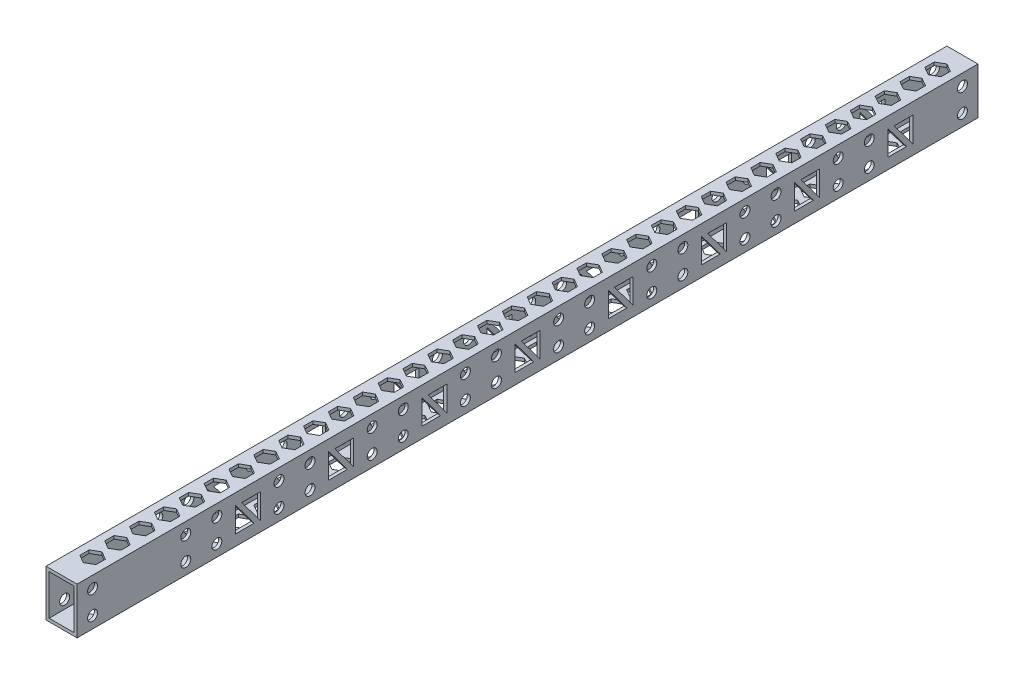
SolidWorks part; units mm, degrees
ref_plane "前视基准面" through (0, 0, 0) normal (0, 0, 1) x (1, 0, 0)
ref_plane "上视基准面" through (0, 0, 0) normal (0, 1, 0) x (1, 0, 0)
ref_plane "右视基准面" through (0, 0, 0) normal (1, 0, 0) x (0, 0, -1)
other "Configuration Table"
sketch "草图1" plane through (0, 0, 0) normal (0, 0, 1) x (1, 0, 0)
  line L1 (0, 0) -> (10, 0)
  line L2 (0, 0) -> (0, -15)
  line L3 (0, -15) -> (10, -15)
  line L4 (10, 0) -> (10, -15)
  dimension "D1" = 10
  dimension "D2" = 15
extrude "拉伸-薄壁1" add sketch "草图1" along normal blind 290 thin
sketch "草图2" plane through (10, 0, 0) normal (1, 0, 0) x (0, 0, -1)
  line L0 (-145, 0) -> (-145, -15) construction
  line L1 (-290, 0) -> (0, 0) construction
  line L3 (-290, -15) -> (0, -15) construction
  line L5 (-290, -7.5) -> (-285, -7.5) construction
  line L6 (-290, -15) -> (-290, 0) construction
  line L7 (-285, -7.5) -> (-285, 0) construction
  line L8 (-5, -7.5) -> (-5, 0) construction
  line L9 (0, -7.5) -> (-5, -7.5) construction
  line L10 (-250, 0) -> (-250, -15) construction
  line L11 (-239, -3.5) -> (-239, -11.5)
  line L12 (-239, -11.5) -> (-233, -11.5)
  line L13 (-233, -11.5) -> (-239, -3.5)
  line L14 (-237, -3.75) -> (-231, -3.75)
  line L15 (-231, -3.75) -> (-231, -11.75)
  line L16 (-231, -11.75) -> (-237, -3.75)
  line L17 (-201, -3.75) -> (-201, -11.75)
  line L18 (-207, -3.75) -> (-201, -3.75)
  line L19 (-201, -11.75) -> (-207, -3.75)
  line L20 (-203, -11.5) -> (-209, -3.5)
  line L21 (-209, -3.5) -> (-209, -11.5)
  line L22 (-209, -11.5) -> (-203, -11.5)
  line L23 (-171, -3.75) -> (-171, -11.75)
  line L24 (-177, -3.75) -> (-171, -3.75)
  line L25 (-171, -11.75) -> (-177, -3.75)
  line L26 (-173, -11.5) -> (-179, -3.5)
  line L27 (-179, -3.5) -> (-179, -11.5)
  line L28 (-179, -11.5) -> (-173, -11.5)
  line L29 (-141, -3.75) -> (-141, -11.75)
  line L30 (-147, -3.75) -> (-141, -3.75)
  line L31 (-141, -11.75) -> (-147, -3.75)
  line L32 (-143, -11.5) -> (-149, -3.5)
  line L33 (-149, -3.5) -> (-149, -11.5)
  line L34 (-149, -11.5) -> (-143, -11.5)
  line L35 (-111, -3.75) -> (-111, -11.75)
  line L36 (-117, -3.75) -> (-111, -3.75)
  line L37 (-111, -11.75) -> (-117, -3.75)
  line L38 (-113, -11.5) -> (-119, -3.5)
  line L39 (-119, -3.5) -> (-119, -11.5)
  line L40 (-119, -11.5) -> (-113, -11.5)
  line L41 (-81, -3.75) -> (-81, -11.75)
  line L42 (-87, -3.75) -> (-81, -3.75)
  line L43 (-81, -11.75) -> (-87, -3.75)
  line L44 (-83, -11.5) -> (-89, -3.5)
  line L45 (-89, -3.5) -> (-89, -11.5)
  line L46 (-89, -11.5) -> (-83, -11.5)
  line L47 (-51, -3.75) -> (-51, -11.75)
  line L48 (-57, -3.75) -> (-51, -3.75)
  line L49 (-51, -11.75) -> (-57, -3.75)
  line L50 (-53, -11.5) -> (-59, -3.5)
  line L51 (-59, -3.5) -> (-59, -11.5)
  line L52 (-59, -11.5) -> (-53, -11.5)
  line L53 (-21, -3.75) -> (-21, -11.75)
  line L54 (-27, -3.75) -> (-21, -3.75)
  line L55 (-21, -11.75) -> (-27, -3.75)
  line L56 (-23, -11.5) -> (-29, -3.5)
  line L57 (-29, -3.5) -> (-29, -11.5)
  line L58 (-29, -11.5) -> (-23, -11.5)
  circle A4 centre (-285, -3.75) radius 1.6
  circle A5 centre (-285, -11.25) radius 1.6
  circle A6 centre (-5, -11.25) radius 1.6
  circle A7 centre (-5, -3.75) radius 1.6
  circle A8 centre (-255, -3.75) radius 1.6
  circle A9 centre (-255, -11.25) radius 1.6
  circle A10 centre (-245, -11.25) radius 1.6
  circle A11 centre (-245, -3.75) radius 1.6
  circle A12 centre (-225, -3.75) radius 1.6
  circle A13 centre (-215, -3.75) radius 1.6
  circle A14 centre (-215, -11.25) radius 1.6
  circle A15 centre (-225, -11.25) radius 1.6
  circle A16 centre (-195, -3.75) radius 1.6
  circle A17 centre (-185, -3.75) radius 1.6
  circle A18 centre (-185, -11.25) radius 1.6
  circle A19 centre (-195, -11.25) radius 1.6
  circle A20 centre (-165, -3.75) radius 1.6
  circle A21 centre (-155, -3.75) radius 1.6
  circle A22 centre (-155, -11.25) radius 1.6
  circle A23 centre (-165, -11.25) radius 1.6
  circle A24 centre (-135, -3.75) radius 1.6
  circle A25 centre (-125, -3.75) radius 1.6
  circle A26 centre (-125, -11.25) radius 1.6
  circle A27 centre (-135, -11.25) radius 1.6
  circle A28 centre (-105, -3.75) radius 1.6
  circle A29 centre (-95, -3.75) radius 1.6
  circle A30 centre (-95, -11.25) radius 1.6
  circle A31 centre (-105, -11.25) radius 1.6
  circle A32 centre (-75, -3.75) radius 1.6
  circle A33 centre (-65, -3.75) radius 1.6
  circle A34 centre (-65, -11.25) radius 1.6
  circle A35 centre (-75, -11.25) radius 1.6
  circle A36 centre (-45, -3.75) radius 1.6
  circle A37 centre (-35, -3.75) radius 1.6
  circle A38 centre (-35, -11.25) radius 1.6
  circle A39 centre (-45, -11.25) radius 1.6
  dimension "D1" = 40
  dimension "D6" = 3.2
  dimension "D2" = 3.2
  dimension "D3" = 3.75
  dimension "D4" = 5
  dimension "D5" = 5
  dimension "D7" = 3.75
  dimension "D9" = 30
  dimension "D10" = 6
  dimension "D11" = 8
  dimension "D12" = 6
  dimension "D13" = 8
  dimension "D14" = 11
  dimension "D15" = 6
  dimension "D17" = 30
  dimension "D8" = 8
  dimension "D16" = 8
extrude "切除-拉伸1" cut sketch "草图2" against normal through all
sketch "草图3" plane through (0, 0, 0) normal (0, 1, 0) x (1, 0, 0)
  line L0 (5, -8) -> (5, 0) construction
  line L1 (5, -11) -> (7.5981, -9.5)
  line L2 (7.5981, -9.5) -> (7.5981, -6.5)
  line L3 (7.5981, -6.5) -> (5, -5)
  line L4 (5, -5) -> (2.4019, -6.5)
  line L5 (2.4019, -6.5) -> (2.4019, -9.5)
  line L6 (2.4019, -9.5) -> (5, -11)
  line L7 (10, 0) -> (0, 0) construction
  line L8 (5, -13) -> (2.4019, -14.5)
  line L9 (7.5981, -14.5) -> (5, -13)
  line L10 (7.5981, -17.5) -> (7.5981, -14.5)
  line L11 (2.4019, -14.5) -> (2.4019, -17.5)
  line L12 (2.4019, -17.5) -> (5, -19)
  line L13 (5, -19) -> (7.5981, -17.5)
  line L14 (5, -21) -> (2.4019, -22.5)
  line L15 (7.5981, -22.5) -> (5, -21)
  line L16 (7.5981, -25.5) -> (7.5981, -22.5)
  line L17 (2.4019, -22.5) -> (2.4019, -25.5)
  line L18 (2.4019, -25.5) -> (5, -27)
  line L19 (5, -27) -> (7.5981, -25.5)
  line L20 (5, -29) -> (2.4019, -30.5)
  line L21 (7.5981, -30.5) -> (5, -29)
  line L22 (7.5981, -33.5) -> (7.5981, -30.5)
  line L23 (2.4019, -30.5) -> (2.4019, -33.5)
  line L24 (2.4019, -33.5) -> (5, -35)
  line L25 (5, -35) -> (7.5981, -33.5)
  line L26 (5, -37) -> (2.4019, -38.5)
  line L27 (7.5981, -38.5) -> (5, -37)
  line L28 (7.5981, -41.5) -> (7.5981, -38.5)
  line L29 (2.4019, -38.5) -> (2.4019, -41.5)
  line L30 (2.4019, -41.5) -> (5, -43)
  line L31 (5, -43) -> (7.5981, -41.5)
  line L32 (5, -45) -> (2.4019, -46.5)
  line L33 (7.5981, -46.5) -> (5, -45)
  line L34 (7.5981, -49.5) -> (7.5981, -46.5)
  line L35 (2.4019, -46.5) -> (2.4019, -49.5)
  line L36 (2.4019, -49.5) -> (5, -51)
  line L37 (5, -51) -> (7.5981, -49.5)
  line L38 (5, -53) -> (2.4019, -54.5)
  line L39 (7.5981, -54.5) -> (5, -53)
  line L40 (7.5981, -57.5) -> (7.5981, -54.5)
  line L41 (2.4019, -54.5) -> (2.4019, -57.5)
  line L42 (2.4019, -57.5) -> (5, -59)
  line L43 (5, -59) -> (7.5981, -57.5)
  line L44 (5, -61) -> (2.4019, -62.5)
  line L45 (7.5981, -62.5) -> (5, -61)
  line L46 (7.5981, -65.5) -> (7.5981, -62.5)
  line L47 (2.4019, -62.5) -> (2.4019, -65.5)
  line L48 (2.4019, -65.5) -> (5, -67)
  line L49 (5, -67) -> (7.5981, -65.5)
  line L50 (5, -69) -> (2.4019, -70.5)
  line L51 (7.5981, -70.5) -> (5, -69)
  line L52 (7.5981, -73.5) -> (7.5981, -70.5)
  line L53 (2.4019, -70.5) -> (2.4019, -73.5)
  line L54 (2.4019, -73.5) -> (5, -75)
  line L55 (5, -75) -> (7.5981, -73.5)
  line L56 (5, -77) -> (2.4019, -78.5)
  line L57 (7.5981, -78.5) -> (5, -77)
  line L58 (7.5981, -81.5) -> (7.5981, -78.5)
  line L59 (2.4019, -78.5) -> (2.4019, -81.5)
  line L60 (2.4019, -81.5) -> (5, -83)
  line L61 (5, -83) -> (7.5981, -81.5)
  line L62 (5, -85) -> (2.4019, -86.5)
  line L63 (7.5981, -86.5) -> (5, -85)
  line L64 (7.5981, -89.5) -> (7.5981, -86.5)
  line L65 (2.4019, -86.5) -> (2.4019, -89.5)
  line L66 (2.4019, -89.5) -> (5, -91)
  line L67 (5, -91) -> (7.5981, -89.5)
  line L68 (5, -93) -> (2.4019, -94.5)
  line L69 (7.5981, -94.5) -> (5, -93)
  line L70 (7.5981, -97.5) -> (7.5981, -94.5)
  line L71 (2.4019, -94.5) -> (2.4019, -97.5)
  line L72 (2.4019, -97.5) -> (5, -99)
  line L73 (5, -99) -> (7.5981, -97.5)
  line L74 (5, -101) -> (2.4019, -102.5)
  line L75 (7.5981, -102.5) -> (5, -101)
  line L76 (7.5981, -105.5) -> (7.5981, -102.5)
  line L77 (2.4019, -102.5) -> (2.4019, -105.5)
  line L78 (2.4019, -105.5) -> (5, -107)
  line L79 (5, -107) -> (7.5981, -105.5)
  line L80 (5, -109) -> (2.4019, -110.5)
  line L81 (7.5981, -110.5) -> (5, -109)
  line L82 (7.5981, -113.5) -> (7.5981, -110.5)
  line L83 (2.4019, -110.5) -> (2.4019, -113.5)
  line L84 (2.4019, -113.5) -> (5, -115)
  line L85 (5, -115) -> (7.5981, -113.5)
  line L86 (5, -117) -> (2.4019, -118.5)
  line L87 (7.5981, -118.5) -> (5, -117)
  line L88 (7.5981, -121.5) -> (7.5981, -118.5)
  line L89 (2.4019, -118.5) -> (2.4019, -121.5)
  line L90 (2.4019, -121.5) -> (5, -123)
  line L91 (5, -123) -> (7.5981, -121.5)
  line L92 (5, -125) -> (2.4019, -126.5)
  line L93 (7.5981, -126.5) -> (5, -125)
  line L94 (7.5981, -129.5) -> (7.5981, -126.5)
  line L95 (2.4019, -126.5) -> (2.4019, -129.5)
  line L96 (2.4019, -129.5) -> (5, -131)
  line L97 (5, -131) -> (7.5981, -129.5)
  line L98 (5, -133) -> (2.4019, -134.5)
  line L99 (7.5981, -134.5) -> (5, -133)
  line L100 (7.5981, -137.5) -> (7.5981, -134.5)
  line L101 (2.4019, -134.5) -> (2.4019, -137.5)
  line L102 (2.4019, -137.5) -> (5, -139)
  line L103 (5, -139) -> (7.5981, -137.5)
  line L104 (5, -141) -> (2.4019, -142.5)
  line L105 (7.5981, -142.5) -> (5, -141)
  line L106 (7.5981, -145.5) -> (7.5981, -142.5)
  line L107 (2.4019, -142.5) -> (2.4019, -145.5)
  line L108 (2.4019, -145.5) -> (5, -147)
  line L109 (5, -147) -> (7.5981, -145.5)
  line L110 (5, -149) -> (2.4019, -150.5)
  line L111 (7.5981, -150.5) -> (5, -149)
  line L112 (7.5981, -153.5) -> (7.5981, -150.5)
  line L113 (2.4019, -150.5) -> (2.4019, -153.5)
  line L114 (2.4019, -153.5) -> (5, -155)
  line L115 (5, -155) -> (7.5981, -153.5)
  line L116 (5, -157) -> (2.4019, -158.5)
  line L117 (7.5981, -158.5) -> (5, -157)
  line L118 (7.5981, -161.5) -> (7.5981, -158.5)
  line L119 (2.4019, -158.5) -> (2.4019, -161.5)
  line L120 (2.4019, -161.5) -> (5, -163)
  line L121 (5, -163) -> (7.5981, -161.5)
  line L122 (5, -165) -> (2.4019, -166.5)
  line L123 (7.5981, -166.5) -> (5, -165)
  line L124 (7.5981, -169.5) -> (7.5981, -166.5)
  line L125 (2.4019, -166.5) -> (2.4019, -169.5)
  line L126 (2.4019, -169.5) -> (5, -171)
  line L127 (5, -171) -> (7.5981, -169.5)
  line L128 (5, -173) -> (2.4019, -174.5)
  line L129 (7.5981, -174.5) -> (5, -173)
  line L130 (7.5981, -177.5) -> (7.5981, -174.5)
  line L131 (2.4019, -174.5) -> (2.4019, -177.5)
  line L132 (2.4019, -177.5) -> (5, -179)
  line L133 (5, -179) -> (7.5981, -177.5)
  line L134 (5, -181) -> (2.4019, -182.5)
  line L135 (7.5981, -182.5) -> (5, -181)
  line L136 (7.5981, -185.5) -> (7.5981, -182.5)
  line L137 (2.4019, -182.5) -> (2.4019, -185.5)
  line L138 (2.4019, -185.5) -> (5, -187)
  line L139 (5, -187) -> (7.5981, -185.5)
  line L140 (5, -189) -> (2.4019, -190.5)
  line L141 (7.5981, -190.5) -> (5, -189)
  line L142 (7.5981, -193.5) -> (7.5981, -190.5)
  line L143 (2.4019, -190.5) -> (2.4019, -193.5)
  line L144 (2.4019, -193.5) -> (5, -195)
  line L145 (5, -195) -> (7.5981, -193.5)
  line L146 (5, -197) -> (2.4019, -198.5)
  line L147 (7.5981, -198.5) -> (5, -197)
  line L148 (7.5981, -201.5) -> (7.5981, -198.5)
  line L149 (2.4019, -198.5) -> (2.4019, -201.5)
  line L150 (2.4019, -201.5) -> (5, -203)
  line L151 (5, -203) -> (7.5981, -201.5)
  line L152 (5, -205) -> (2.4019, -206.5)
  line L153 (7.5981, -206.5) -> (5, -205)
  line L154 (7.5981, -209.5) -> (7.5981, -206.5)
  line L155 (2.4019, -206.5) -> (2.4019, -209.5)
  line L156 (2.4019, -209.5) -> (5, -211)
  line L157 (5, -211) -> (7.5981, -209.5)
  line L158 (5, -213) -> (2.4019, -214.5)
  line L159 (7.5981, -214.5) -> (5, -213)
  line L160 (7.5981, -217.5) -> (7.5981, -214.5)
  line L161 (2.4019, -214.5) -> (2.4019, -217.5)
  line L162 (2.4019, -217.5) -> (5, -219)
  line L163 (5, -219) -> (7.5981, -217.5)
  line L164 (5, -221) -> (2.4019, -222.5)
  line L165 (7.5981, -222.5) -> (5, -221)
  line L166 (7.5981, -225.5) -> (7.5981, -222.5)
  line L167 (2.4019, -222.5) -> (2.4019, -225.5)
  line L168 (2.4019, -225.5) -> (5, -227)
  line L169 (5, -227) -> (7.5981, -225.5)
  line L170 (5, -229) -> (2.4019, -230.5)
  line L171 (7.5981, -230.5) -> (5, -229)
  line L172 (7.5981, -233.5) -> (7.5981, -230.5)
  line L173 (2.4019, -230.5) -> (2.4019, -233.5)
  line L174 (2.4019, -233.5) -> (5, -235)
  line L175 (5, -235) -> (7.5981, -233.5)
  line L176 (5, -237) -> (2.4019, -238.5)
  line L177 (7.5981, -238.5) -> (5, -237)
  line L178 (7.5981, -241.5) -> (7.5981, -238.5)
  line L179 (2.4019, -238.5) -> (2.4019, -241.5)
  line L180 (2.4019, -241.5) -> (5, -243)
  line L181 (5, -243) -> (7.5981, -241.5)
  line L182 (5, -245) -> (2.4019, -246.5)
  line L183 (7.5981, -246.5) -> (5, -245)
  line L184 (7.5981, -249.5) -> (7.5981, -246.5)
  line L185 (2.4019, -246.5) -> (2.4019, -249.5)
  line L186 (2.4019, -249.5) -> (5, -251)
  line L187 (5, -251) -> (7.5981, -249.5)
  line L188 (5, -253) -> (2.4019, -254.5)
  line L189 (7.5981, -254.5) -> (5, -253)
  line L190 (7.5981, -257.5) -> (7.5981, -254.5)
  line L191 (2.4019, -254.5) -> (2.4019, -257.5)
  line L192 (2.4019, -257.5) -> (5, -259)
  line L193 (5, -259) -> (7.5981, -257.5)
  line L194 (5, -261) -> (2.4019, -262.5)
  line L195 (7.5981, -262.5) -> (5, -261)
  line L196 (7.5981, -265.5) -> (7.5981, -262.5)
  line L197 (2.4019, -262.5) -> (2.4019, -265.5)
  line L198 (2.4019, -265.5) -> (5, -267)
  line L199 (5, -267) -> (7.5981, -265.5)
  line L200 (5, -269) -> (2.4019, -270.5)
  line L201 (7.5981, -270.5) -> (5, -269)
  line L202 (7.5981, -273.5) -> (7.5981, -270.5)
  line L203 (2.4019, -270.5) -> (2.4019, -273.5)
  line L204 (2.4019, -273.5) -> (5, -275)
  line L205 (5, -275) -> (7.5981, -273.5)
  line L206 (5, -277) -> (2.4019, -278.5)
  line L207 (7.5981, -278.5) -> (5, -277)
  line L208 (7.5981, -281.5) -> (7.5981, -278.5)
  line L209 (2.4019, -278.5) -> (2.4019, -281.5)
  line L210 (2.4019, -281.5) -> (5, -283)
  line L211 (5, -283) -> (7.5981, -281.5)
  circle A0 centre (5, -8) radius 2.5981 construction
  dimension "D1" = 8
  dimension "D2" = 3
  dimension "D4" = 8
  dimension "D3" = 35
extrude "切除-拉伸2" cut sketch "草图3" against normal through all
